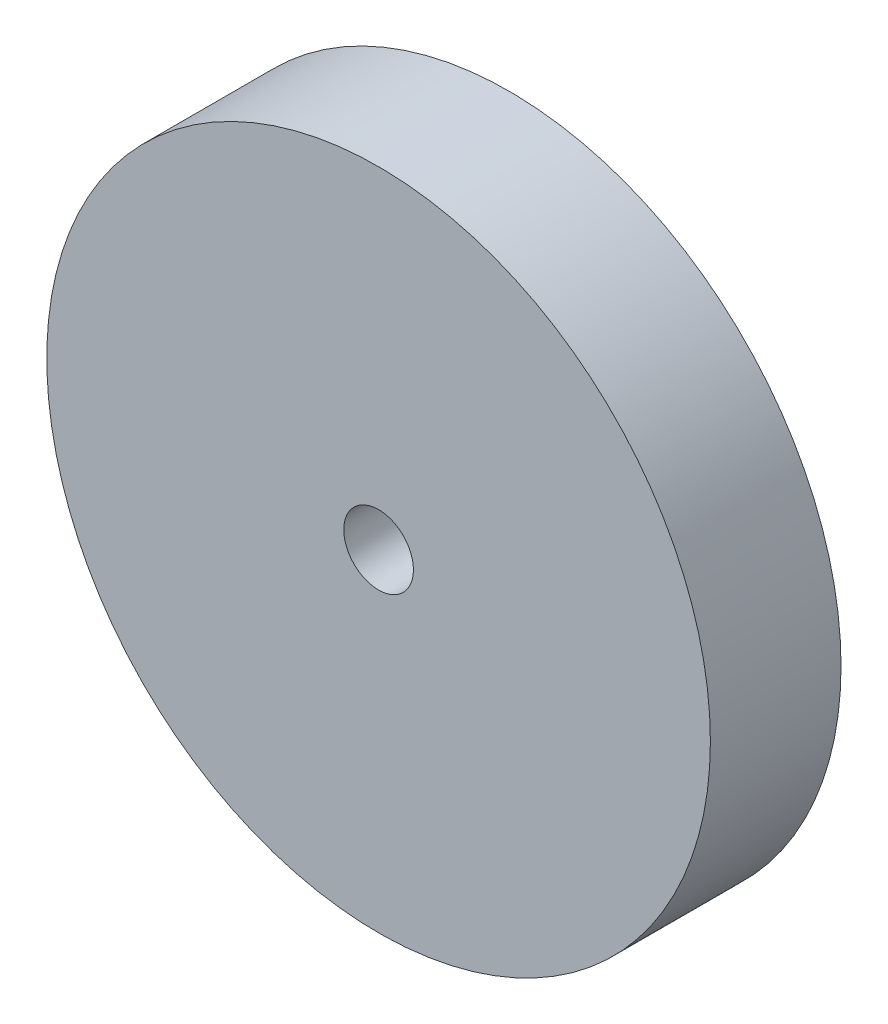
SolidWorks part; units mm, degrees
material "Oak"
ref_plane "Front Plane" through (0, 0, 0) normal (0, 0, 1) x (1, 0, 0)
ref_plane "Top Plane" through (0, 0, 0) normal (0, 1, 0) x (1, 0, 0)
ref_plane "Right Plane" through (0, 0, 0) normal (1, 0, 0) x (0, 0, -1)
sketch "Sketch1" plane through (0, 0, 0) normal (0, 0, 1) x (1, 0, 0)
  circle A0 centre (0, 0) radius 38.1
  circle A1 centre (0, 0) radius 4
  dimension "D1" = 76.2
  dimension "D2" = 8
extrude "Boss-Extrude1" add sketch "Sketch1" along normal blind 15
